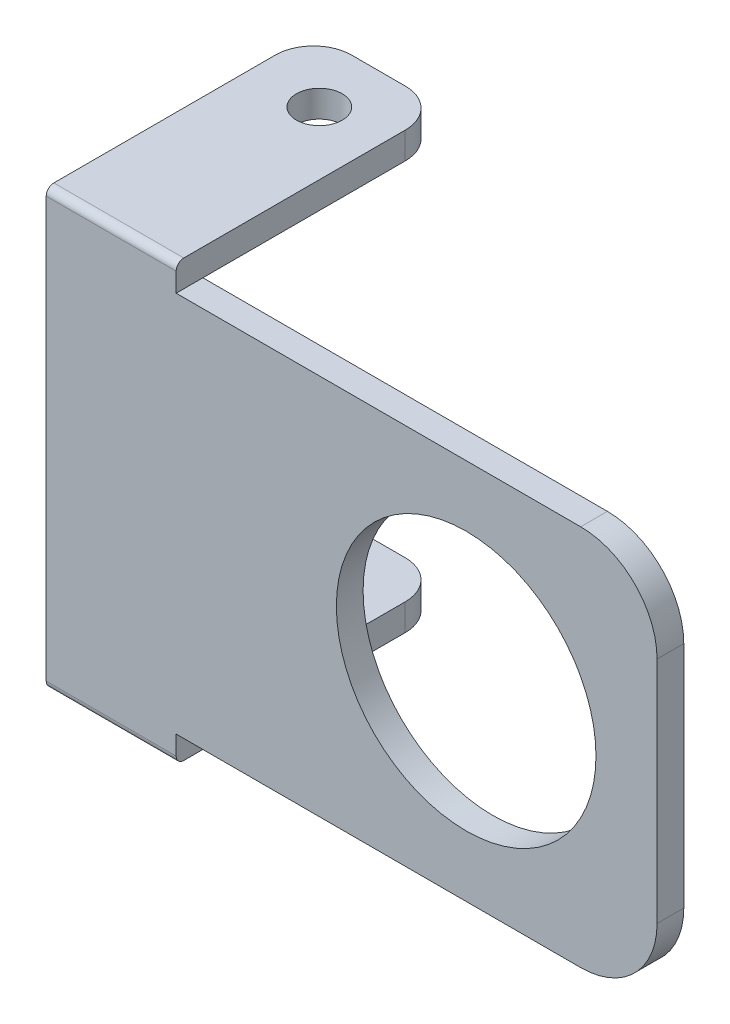
SolidWorks part; units mm, degrees
ref_plane "前视基准面" through (0, 0, 0) normal (0, 0, 1) x (1, 0, 0)
ref_plane "上视基准面" through (0, 0, 0) normal (0, 1, 0) x (1, 0, 0)
ref_plane "右视基准面" through (0, 0, 0) normal (1, 0, 0) x (0, 0, -1)
sketch "草图1" plane through (0, 0, 0) normal (0, 0, 1) x (1, 0, 0)
  line L1 (-40, 25) -> (40, 25)
  line L2 (-40, 25) -> (-40, -25)
  line L3 (-40, -25) -> (40, -25)
  line L4 (40, 25) -> (40, -25)
  line L5 (-40, 25) -> (40, -25) construction
  line L6 (-40, -25) -> (40, 25) construction
  point P0 (0, 0)
  dimension "D1" = 50
  dimension "D2" = 80
extrude "凸台-拉伸1" add sketch "草图1" along normal blind 3.5
sketch "草图2" plane through (0, 0, 0) normal (0, 0, -1) x (-1, 0, 0)
  line L1 (27.9796, -12.4) -> (27.9836, 12.6)
  line L3 (17.9796, 12.4) -> (17.9796, -12.4)
  arc A1 (27.9836, 12.6) -> (17.9796, 12.4) centre (22.9796, 12.6) ccw
  arc A2 (17.9796, -12.4) -> (27.9796, -12.4) centre (22.9796, -12.4) ccw
  dimension "D1" = 25
extrude "切除-拉伸1" cut sketch "草图2" against normal blind 3
sketch "草图12" plane through (0, 25, 0) normal (0, 1, 0) x (1, 0, 0)
  line L3 (-22.9796, -3.5) -> (-22.9796, 31.5)
  line L4 (40, -3.5) -> (-40, -3.5) construction
  line L5 (-22.9796, -3.5) -> (-40, -3.5)
  line L6 (-40, -3.5) -> (-40, 0) construction
  line L7 (-40, -3.5) -> (-40, 31.5)
  line L8 (-22.9796, 31.5) -> (-40, 31.5)
  dimension "D1" = 35
extrude "凸台-拉伸2" add sketch "草图12" along normal blind 3.5
mirror "镜向1" about plane through (0, 0, 0) normal (0, 1, 0) of "凸台-拉伸2"
fillet "圆角1" radius 1 2 edges at (-31.4898, 28.5, 3.5) (-31.4898, -28.5, 3.5)
fillet "圆角2" radius 5 4 edges at (-22.9796, -26.75, -31.5) (-40, -26.75, -31.5) (-40, 26.75, -31.5) (-22.9796, 26.75, -31.5)
sketch "草图13" plane through (0, 28.5, 0) normal (0, 1, 0) x (1, 0, 0)
  line L0 (-22.9796, -2.5) -> (-22.9796, 26.5) construction
  line L2 (-27.9796, 31.5) -> (-35, 31.5) construction
  circle A0 centre (-31.2296, 23.5) radius 3
  dimension "D3" = 6
  dimension "D1" = 8.25
  dimension "D2" = 8
extrude "切除-拉伸2" cut sketch "草图13" against normal blind 10
mirror "镜向2" about plane through (0, 0, 0) normal (0, 1, 0) of "切除-拉伸2"
sketch "草图14" plane through (0, 0, 0) normal (0, 0, -1) x (-1, 0, 0)
  line L0 (-40, 25) -> (22.9796, 25) construction
  line L1 (-40, -25) -> (-40, 25) construction
  circle A0 centre (-15, 0) radius 17
  dimension "D1" = 34
  dimension "D2" = 25
  dimension "D3" = 25
extrude "切除-拉伸3" cut sketch "草图14" against normal blind 8
fillet "圆角3" radius 10 2 edges at (40, -25, 1.75) (40, 25, 1.75)
